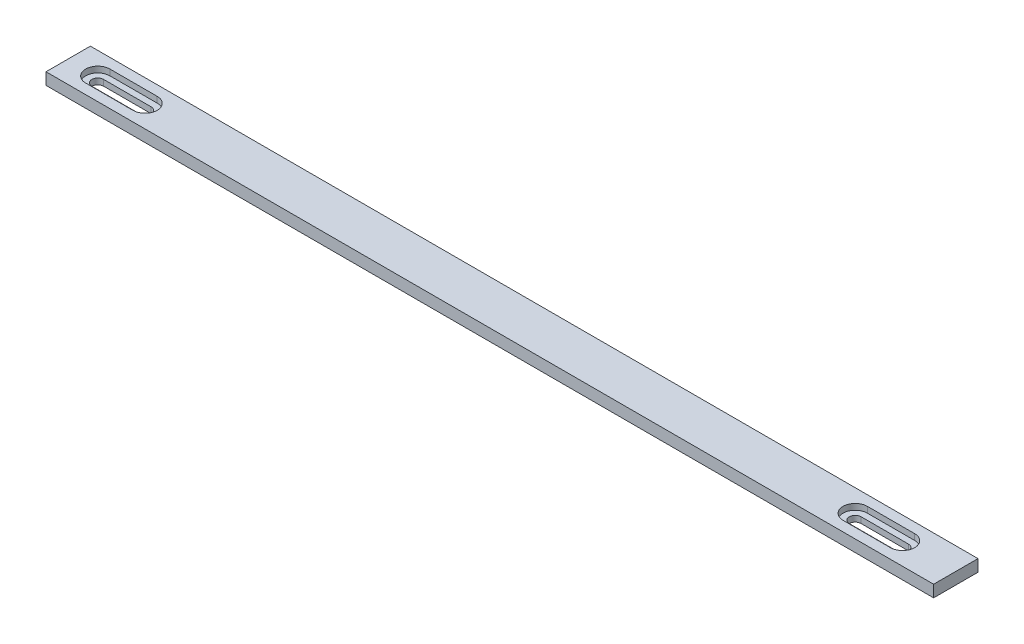
SolidWorks part; units mm, degrees
material "PMMA"
ref_plane "前视基准面" through (0, 0, 0) normal (0, 0, 1) x (1, 0, 0)
ref_plane "上视基准面" through (0, 0, 0) normal (0, 1, 0) x (1, 0, 0)
ref_plane "右视基准面" through (0, 0, 0) normal (1, 0, 0) x (0, 0, -1)
sketch "Sketch1" plane through (0, 0, 0) normal (1, 0, 0) x (0, 0, -1)
  line L0 (0, 0) -> (0, -4)
  line L1 (0, -4) -> (15, -4)
  line L2 (15, -4) -> (15, 0)
  line L3 (15, 0) -> (0, 0)
  dimension "D1" = 15
  dimension "D2" = 4
extrude "Boss-Extrude1" add sketch "Sketch1" along normal blind 300
sketch "Sketch3" plane through (0, 0, 0) normal (0, 1, 0) x (1, 0, 0)
  line L0 (-10.3442, 7.5) -> (315.3615, 7.5) construction
  line L1 (300, 15) -> (0, 15) construction
  line L2 (266, 7.5) -> (282, 7.5) construction
  line L3 (10, 7.5) -> (26, 7.5) construction
  line L4 (10, 9.5) -> (26, 9.5)
  line L5 (10, 5.5) -> (26, 5.5)
  line L6 (0, 15) -> (0, 0) construction
  line L7 (266, 9.5) -> (282, 9.5)
  line L8 (266, 5.5) -> (282, 5.5)
  arc A1 (10, 9.5) -> (10, 5.5) centre (10, 7.5) ccw
  arc A2 (26, 5.5) -> (26, 9.5) centre (26, 7.5) ccw
  arc A3 (266, 9.5) -> (266, 5.5) centre (266, 7.5) ccw
  arc A4 (282, 5.5) -> (282, 9.5) centre (282, 7.5) ccw
  point P6 (18, 7.5)
  point P17 (274, 7.5)
  dimension "D2" = 2
  dimension "D1" = 7.5
  dimension "D3" = 10
  dimension "D4" = 16
  dimension "D6" = 272
  dimension "D5" = 2
extrude "Cut-Extrude1" cut sketch "Sketch3" against normal through all
sketch "Sketch4" plane through (0, 0, 0) normal (0, 1, 0) x (1, 0, 0)
  line L0 (10, 7.5) -> (26, 7.5) construction
  line L1 (10, 11.6) -> (26, 11.6)
  line L2 (10, 3.4) -> (26, 3.4)
  line L3 (266, 7.5) -> (282, 7.5) construction
  line L4 (266, 11.6) -> (282, 11.6)
  line L5 (266, 3.4) -> (282, 3.4)
  arc A0 (10, 11.6) -> (10, 3.4) centre (10, 7.5) ccw
  arc A1 (26, 3.4) -> (26, 11.6) centre (26, 7.5) ccw
  arc A2 (266, 11.6) -> (266, 3.4) centre (266, 7.5) ccw
  arc A3 (282, 3.4) -> (282, 11.6) centre (282, 7.5) ccw
  point P4 (18, 7.5)
  point P13 (274, 7.5)
  dimension "D1" = 4.1
  dimension "D3" = 256
  dimension "D2" = 2
extrude "Cut-Extrude2" cut sketch "Sketch4" against normal blind 2
